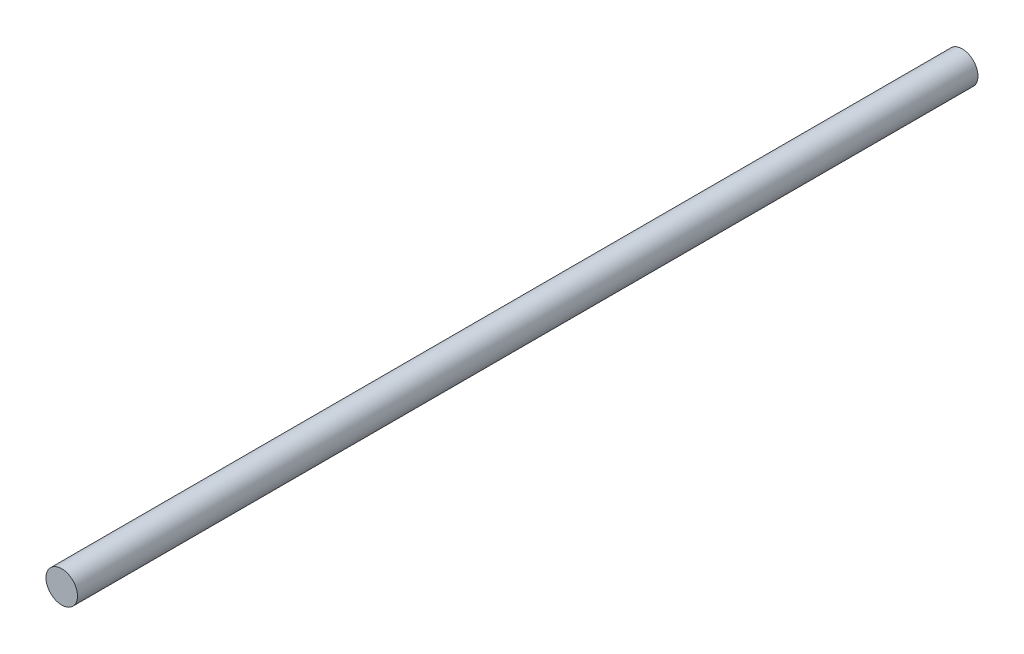
SolidWorks part; units mm, degrees
ref_plane "Спереди" through (0, 0, 0) normal (0, 0, 1) x (1, 0, 0)
ref_plane "Сверху" through (0, 0, 0) normal (0, 1, 0) x (1, 0, 0)
ref_plane "Справа" through (0, 0, 0) normal (1, 0, 0) x (0, 0, -1)
sketch "Эскиз1" plane through (0, 0, 0) normal (0, 0, 1) x (1, 0, 0)
  circle A0 centre (0, 0) radius 1.75
extrude "Вытянуть1" add sketch "Эскиз1" along normal blind 100
